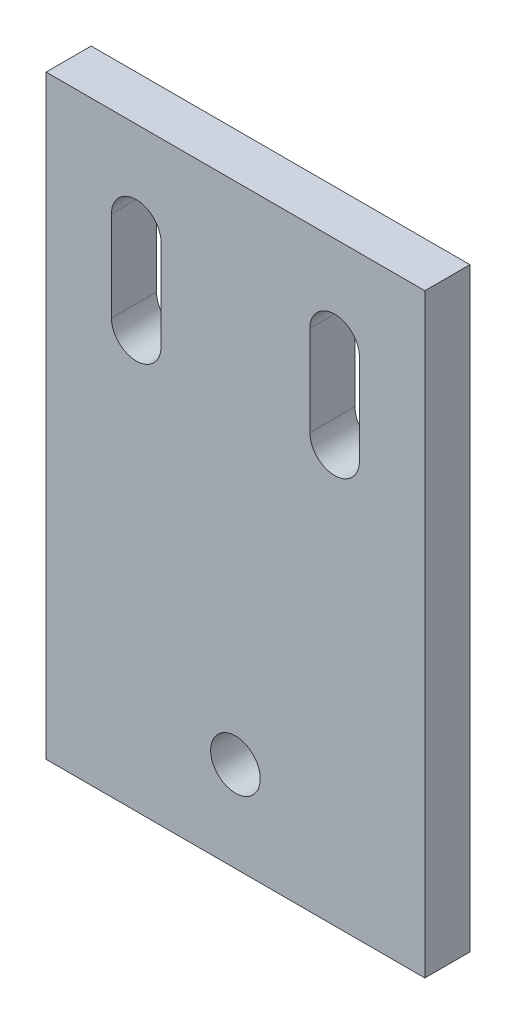
SolidWorks part; units mm, degrees
ref_plane "Plan de face" through (0, 0, 0) normal (0, 0, 1) x (1, 0, 0)
ref_plane "Plan de dessus" through (0, 0, 0) normal (0, 1, 0) x (1, 0, 0)
ref_plane "Plan de droite" through (0, 0, 0) normal (1, 0, 0) x (0, 0, -1)
sketch "Sketch1" plane through (0, 0, 0) normal (0, 0, 1) x (1, 0, 0)
  line L1 (21, -33) -> (-21, -33)
  line L2 (21, -33) -> (21, 33)
  line L3 (21, 33) -> (-21, 33)
  line L4 (-21, -33) -> (-21, 33)
  line L5 (21, -33) -> (-21, 33) construction
  line L6 (21, 33) -> (-21, -33) construction
  point P0 (0, 0)
  dimension "D1" = 42
  dimension "D2" = 66
extrude "Boss-Extrude1" add sketch "Sketch1" along normal blind 5
hole_wizard "Dégagement M51" positions "Sketch3" profile "Sketch4" hole size "M5" standard "ISO" end condition through all
sketch "Sketch3" plane through (0, 0, 5) normal (0, 0, 1) x (1, 0, 0)
  line L0 (21, -33) -> (21, 33) construction
  line L1 (-21, 33) -> (-21, -33) construction
  line L2 (21, 33) -> (-21, 33) construction
  line L3 (-21, -33) -> (21, -33) construction
  point P0 (11, 18)
  point P2 (-11, 18)
  point P11 (0, -23)
  dimension "D1" = 10
  dimension "D2" = 10
  dimension "D3" = 15
  dimension "D4" = 15
  dimension "D5" = 10
sketch "Sketch4" plane through (11, 18, 5) normal (1, 0, 0) x (0, -1, 0)
  line L0 (0, 0) -> (0, 5)
  line L1 (0, 5) -> (2.75, 5)
  line L2 (2.75, 5) -> (2.75, 0)
  line L5 (2.75, 0) -> (0, 0)
  line L11 (0, -6.35) -> (0, 107.95) construction
  dimension "Diamètre du perçage jusqu'au prochain" = 5.5
  dimension "Profondeur du perçage jusqu'au prochain" = 5
sketch "Sketch5" plane through (0, 0, 5) normal (0, 0, 1) x (1, 0, 0)
  line L0 (-11, 13) -> (-11, 23) construction
  line L1 (-13.75, 13) -> (-13.75, 23)
  line L2 (-8.25, 13) -> (-8.25, 23)
  line L3 (11, 13) -> (11, 23) construction
  line L4 (8.25, 13) -> (8.25, 23)
  line L5 (13.75, 13) -> (13.75, 23)
  arc A0 (-13.75, 13) -> (-8.25, 13) centre (-11, 13) ccw
  arc A1 (-8.25, 23) -> (-13.75, 23) centre (-11, 23) ccw
  arc A2 (8.25, 13) -> (13.75, 13) centre (11, 13) ccw
  arc A3 (13.75, 23) -> (8.25, 23) centre (11, 23) ccw
  circle A4 centre (11, 18) radius 2.75 construction
  circle A5 centre (-11, 18) radius 2.75 construction
  point P2 (-11, 18)
  point P9 (11, 18)
  dimension "D1" = 10
  dimension "D2" = 10
extrude "Cut-Extrude1" cut sketch "Sketch5" against normal through all
